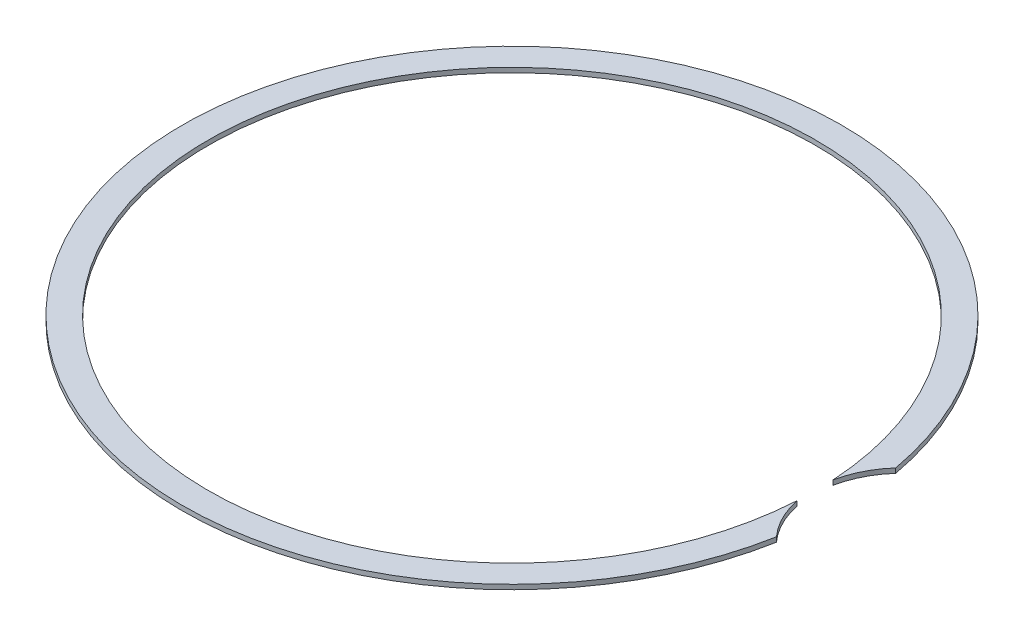
SolidWorks part; units mm, degrees
ref_plane "前视基准面" through (0, 0, 0) normal (0, 0, 1) x (1, 0, 0)
ref_plane "上视基准面" through (0, 0, 0) normal (0, 1, 0) x (1, 0, 0)
ref_plane "右视基准面" through (0, 0, 0) normal (1, 0, 0) x (0, 0, -1)
other "Configuration Table"
sketch "草图1" plane through (0, 0, 0) normal (0, 1, 0) x (1, 0, 0)
  line L0 (0, 0) -> (41.5, 0) construction
  arc A0 (32.1935, 1.9077) -> (32.1935, -1.9077) centre (0, 0) ccw
  arc A1 (34.4217, 6.3362) -> (34.4217, -6.3362) centre (0, 0) ccw
  arc A2 (34.4217, 6.3362) -> (32.1935, 1.9077) centre (41.5, 0) ccw
  arc A3 (32.1935, -1.9077) -> (34.4217, -6.3362) centre (41.5, 0) ccw
  dimension "D1" = 64.5
  dimension "D2" = 70
  dimension "D4" = 19
  dimension "D3" = 41.5
extrude "凸台-拉伸1" add sketch "草图1" along normal blind 0.5
